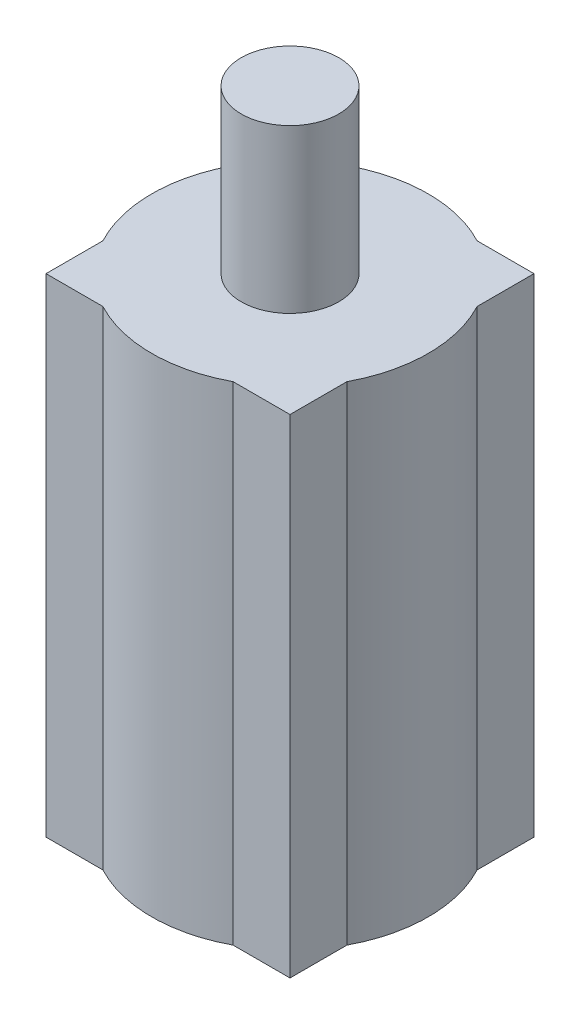
SolidWorks part; units mm, degrees
material "ASTM A36 Steel"
ref_plane "Front Plane" through (0, 0, 0) normal (0, 0, 1) x (1, 0, 0)
ref_plane "Top Plane" through (0, 0, 0) normal (0, 1, 0) x (1, 0, 0)
ref_plane "Right Plane" through (0, 0, 0) normal (1, 0, 0) x (0, 0, -1)
sketch "Sketch1" plane through (0, 0, 0) normal (0, 1, 0) x (1, 0, 0)
  line L1 (-7.5, -7.5) -> (7.5, -7.5)
  line L2 (-7.5, -7.5) -> (-7.5, 7.5)
  line L3 (-7.5, 7.5) -> (7.5, 7.5)
  line L4 (7.5, -7.5) -> (7.5, 7.5)
  line L5 (-7.5, -7.5) -> (7.5, 7.5) construction
  line L6 (-7.5, 7.5) -> (7.5, -7.5) construction
  circle A0 centre (0, 0) radius 8.5
  dimension "17" = 17
  dimension "D2" = 15
extrude "Boss-Extrude1" add sketch "Sketch1" along normal blind 30 contours L3 A0 | L2 A0 | L1 A0 | L4 A0
sketch "Sketch2" plane through (0, 30, 0) normal (0, 1, 0) x (1, 0, 0)
  circle A0 centre (0, 0) radius 3
  dimension "D1" = 6
extrude "Boss-Extrude2" add sketch "Sketch2" along normal blind 10
